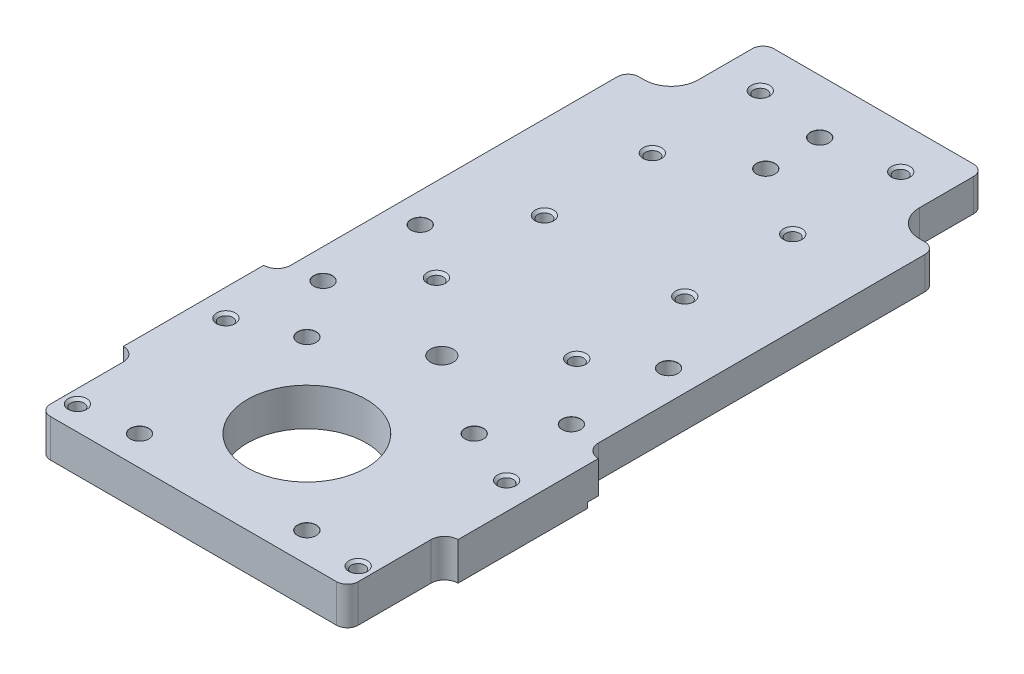
SolidWorks part; units mm, degrees
ref_plane "Top" through (0, 0, 0) normal (0, 0, 1) x (1, 0, 0)
ref_plane "Front" through (0, 0, 0) normal (0, 1, 0) x (1, 0, 0)
ref_plane "Right" through (0, 0, 0) normal (1, 0, 0) x (0, 0, -1)
sketch "Plate Main Sketch" plane through (-158.0855, 0, 24.6791) normal (0, 1, 0) x (-1, 0, 0)
  line L1 (-178.5855, -24.6791) -> (-137.5855, -24.6791)
  line L2 (-127.0855, 57.3209) -> (-127.0855, 83.3209)
  line L3 (-129.5855, 101.3209) -> (-186.5855, 101.3209)
  line L4 (-129.5855, 101.3209) -> (-129.5855, 85.8209)
  line L5 (-158.0855, 101.3209) -> (-158.0855, -24.6791) construction
  line L6 (-178.5855, -12.6791) -> (-178.5855, -24.6791)
  line L7 (-129.5855, 54.8209) -> (-129.5855, -7.6791)
  line L8 (-129.5855, -7.6791) -> (-132.5855, -7.6791)
  line L9 (-137.5855, -12.6791) -> (-137.5855, -24.6791)
  line L10 (-186.5855, -7.6791) -> (-183.5855, -7.6791)
  line L11 (-186.5855, 54.8209) -> (-186.5855, -7.6791)
  line L12 (-189.0855, 57.3209) -> (-189.0855, 83.3209)
  line L13 (-186.5855, 101.3209) -> (-186.5855, 85.8209)
  arc A0 (-129.5855, 85.8209) -> (-127.0855, 83.3209) centre (-127.0855, 85.8209) ccw
  arc A1 (-129.5855, 54.8209) -> (-127.0855, 57.3209) centre (-127.0855, 54.8209) cw
  arc A2 (-132.5855, -7.6791) -> (-137.5855, -12.6791) centre (-132.5855, -12.6791) ccw
  arc A3 (-183.5855, -7.6791) -> (-178.5855, -12.6791) centre (-183.5855, -12.6791) cw
  arc A4 (-186.5855, 54.8209) -> (-189.0855, 57.3209) centre (-189.0855, 54.8209) ccw
  arc A5 (-186.5855, 85.8209) -> (-189.0855, 83.3209) centre (-189.0855, 85.8209) cw
  circle A18 centre (-158.0855, 80.3209) radius 11
  circle A19 centre (-158.0855, 55.3209) radius 2.1117
  dimension "D2" = 5
  dimension "D8" = 22
  dimension "D1" = 2.5
  dimension "D3" = 62
  dimension "D4" = 126
  dimension "D5" = 18
  dimension "D6" = 44
  dimension "D15" = 21
  dimension "D16" = 46
  dimension "D17" = 8
  dimension "D7" = 109
extrude "Extrude Plate Main" add sketch "Plate Main Sketch" along normal blind 7
fillet "Fillet1" radius 2 6 edges at (-28.5, 3.5, 126) (-28.5, 3.5, 17) (-20.5, 3.5, 0) (20.5, 3.5, 0) (28.5, 3.5, 17) (28.5, 3.5, 126)
sketch "Reccess Sketch" plane through (0, 0, 0) normal (0, 1, 0) x (1, 0, 0)
  line L0 (-8.25, 0) -> (-8.25, -81)
  line L1 (-11.25, -84) -> (-31, -84)
  line L2 (-31, -84) -> (-31, 0)
  line L3 (-31, 0) -> (-8.25, 0)
  line L4 (0, 0) -> (0, -84) construction
  line L5 (31, 0) -> (8.25, 0)
  line L6 (8.25, 0) -> (8.25, -81)
  line L7 (31, -84) -> (31, 0)
  line L8 (11.25, -84) -> (31, -84)
  arc A0 (-8.25, -81) -> (-11.25, -84) centre (-11.25, -81) cw
  arc A1 (8.25, -81) -> (11.25, -84) centre (11.25, -81) ccw
  point P7 (-8.25, -84)
  dimension "D4" = 3
  dimension "D1" = 84
  dimension "D2" = 31
  dimension "D3" = 22.75
hole_wizard "M3x0.5 Tapped Hole3" positions "Sketch12" profile "Sketch13" tap size "M3x0.5" standard "ANSI Metric" end condition through all
sketch "Sketch12" plane through (0, 0, 0) normal (0, -1, 0) x (-1, 0, 0)
  line L0 (-13, -8) -> (-13, -68) construction
  line L2 (13, -68) -> (13, -8) construction
  line L4 (26, -121.5) -> (-26, -121.5) construction
  line L5 (-26, -121.5) -> (-26, -94) construction
  line L6 (-26, -94) -> (26, -94) construction
  line L7 (26, -94) -> (26, -121.5) construction
  line L11 (31, -126) -> (-31, -126) construction
  line L12 (31, -126) -> (31, 0) construction
  line L13 (31, 0) -> (-31, 0) construction
  line L14 (-31, -126) -> (-31, 0) construction
  line L15 (0, 0) -> (0, -126) construction
  line L16 (31, -63) -> (-31, -63) construction
  point P0 (-26, -121.5)
  point P2 (-26, -94)
  point P4 (26, -94)
  point P8 (13, -68)
  point P10 (13, -48)
  point P12 (13, -28)
  point P14 (13, -8)
  point P16 (-13, -8)
  point P18 (-13, -28)
  point P20 (-13, -48)
  point P22 (-13, -68)
  point P477 (26, -121.5)
  dimension "D1" = 126
  dimension "D2" = 62
  dimension "D3" = 118
  dimension "D4" = 98
  dimension "D5" = 78
  dimension "D6" = 58
  dimension "D7" = 18
  dimension "D8" = 18
  dimension "D9" = 5
  dimension "D10" = 5
  dimension "D11" = 4.5
  dimension "D12" = 32
sketch "Sketch13" plane through (26, 0, 121.5) normal (1, 0, 0) x (0, 0, -1)
  line L0 (0, 0) -> (0, 7)
  line L1 (0, 7) -> (1.725, 7)
  line L2 (1.25, 6.525) -> (1.25, 0)
  line L5 (1.25, 0) -> (0, 0)
  line L7 (1.725, 7) -> (1.25, 6.525)
  line L8 (-1.725, 7) -> (-1.25, 6.525) construction
  line L11 (0, -6.35) -> (0, 107.95) construction
  dimension "Thru Tap Drill Dia." = 2.5
  dimension "Thru Tap Drill Depth" = 7
  dimension "Far C'Sink Dia." = 3.45
  dimension "Far C'Sink Angle" = 90
cosmetic thread "Hole Thread54" parameters "D2"=3
cosmetic thread "Hole Thread55" parameters "D2"=3
cosmetic thread "Hole Thread56" parameters "D2"=3
cosmetic thread "Hole Thread57" parameters "D2"=3
cosmetic thread "Hole Thread58" parameters "D2"=3
cosmetic thread "Hole Thread59" parameters "D2"=3
cosmetic thread "Hole Thread60" parameters "D2"=3
cosmetic thread "Hole Thread61" parameters "D2"=3
cosmetic thread "Hole Thread62" parameters "D2"=3
cosmetic thread "Hole Thread63" parameters "D2"=3
cosmetic thread "Hole Thread64" parameters "D2"=3
cosmetic thread "Hole Thread65" parameters "D2"=3
hole_wizard "CBORE for M3 SHCS1" positions "Sketch4" profile "Sketch5" counterbore size "M3" standard "ANSI Metric" end condition through all
sketch "Sketch4" plane through (0, 0, 0) normal (0, -1, 0) x (-1, 0, 0)
  line L0 (31, -126) -> (-31, -126) construction
  line L1 (-31, -126) -> (-31, 0) construction
  line L2 (-31, 0) -> (31, 0) construction
  line L3 (31, 0) -> (31, -126) construction
  line L5 (15.5, -120.5) -> (-15.5, -120.5) construction
  line L6 (-15.5, -120.5) -> (-15.5, -89.5) construction
  line L7 (-15.5, -89.5) -> (15.5, -89.5) construction
  line L8 (15.5, -89.5) -> (15.5, -120.5) construction
  line L10 (0, -126) -> (0, 0) construction
  point P0 (15.5, -120.5)
  point P3 (-15.5, -120.5)
  point P6 (-15.5, -89.5)
  point P9 (15.5, -89.5)
  point P12 (23, -79)
  point P15 (-23, -79)
  point P18 (-23, -61)
  point P21 (23, -61)
  point P24 (0, -20)
  point P27 (0, -10)
  point P42 (0, 0)
  point P65 (0, -120.5)
  dimension "D1" = 126
  dimension "D2" = 62
  dimension "D3" = 31
  dimension "D4" = 31
  dimension "D5" = 5.5
  dimension "D6" = 47
  dimension "D7" = 65
  dimension "D8" = 106
  dimension "D9" = 116
  dimension "D10" = 8
  dimension "D11" = 8
sketch "Sketch5" plane through (-15.5, 0, 120.5) normal (1, 0, 0) x (0, 0, -1)
  line L0 (0, 0) -> (0, 7)
  line L1 (1.7, 6.975) -> (1.725, 7)
  line L2 (1.7, 6.975) -> (1.7, 4.5)
  line L3 (1.7, 4.5) -> (3, 4.5)
  line L4 (3, 4.5) -> (3, 0)
  line L5 (3, 0) -> (0, 0)
  line L11 (0, -6.35) -> (0, 107.95) construction
  line L12 (1.725, 7) -> (0, 7)
  line L13 (-1.7, 6.975) -> (-1.725, 7) construction
  dimension "Thru Hole Dia." = 3.4
  dimension "Thru Hole Depth" = 7
  dimension "C'Bore Dia." = 6
  dimension "C'Bore Depth" = 4.5
  dimension "Far C'Sink Dia." = 3.45
  dimension "Far C'Sink Angle" = 90
extrude "Cut Recess" cut sketch "Reccess Sketch" along normal blind 1
sketch "Sketch7" plane through (158.0855, -24.6791, 0) normal (0, 0, -1) x (1, 0, 0)
  line L1 (-178.5855, -24.6791) -> (-137.5855, -24.6791) construction
  line L2 (-127.0855, 57.3209) -> (-127.0855, 83.3209) construction
  line L3 (-129.5855, 101.3209) -> (-186.5855, 101.3209) construction
  line L4 (-129.5855, 101.3209) -> (-129.5855, 85.8209) construction
  line L5 (-158.0855, 101.3209) -> (-158.0855, -24.6791) construction
  line L6 (-178.5855, -12.4678) -> (-178.5855, -24.6791) construction
  line L7 (-129.5855, 54.8209) -> (-129.5855, -7.6791) construction
  line L8 (-129.5855, -7.6791) -> (-132.7968, -7.6791) construction
  line L9 (-137.5855, -12.4678) -> (-137.5855, -24.6791) construction
  line L10 (-186.5855, -7.6791) -> (-183.3743, -7.6791) construction
  line L11 (-186.5855, 54.8209) -> (-186.5855, -7.6791) construction
  line L12 (-189.0855, 57.3209) -> (-189.0855, 83.3209) construction
  line L13 (-186.5855, 101.3209) -> (-186.5855, 85.8209) construction
  line L14 (-173.5855, 95.8209) -> (-142.5855, 95.8209) construction
  line L15 (-142.5855, 95.8209) -> (-142.5855, 64.8209) construction
  line L16 (-142.5855, 64.8209) -> (-173.5855, 64.8209) construction
  line L17 (-173.5855, 64.8209) -> (-173.5855, 95.8209) construction
  arc A0 (-129.5855, 85.8209) -> (-127.0855, 83.3209) centre (-127.0855, 85.8209) ccw construction
  arc A1 (-129.5855, 54.8209) -> (-127.0855, 57.3209) centre (-127.0855, 54.8209) cw construction
  arc A2 (-132.7968, -7.6791) -> (-137.5855, -12.4678) centre (-132.7968, -12.4678) ccw construction
  arc A3 (-183.3743, -7.6791) -> (-178.5855, -12.4678) centre (-183.3743, -12.4678) cw construction
  arc A4 (-186.5855, 54.8209) -> (-189.0855, 57.3209) centre (-189.0855, 54.8209) ccw construction
  arc A5 (-186.5855, 85.8209) -> (-189.0855, 83.3209) centre (-189.0855, 85.8209) cw construction
  circle A6 centre (-142.5855, 95.8209) radius 0.8649
  circle A7 centre (-142.5855, 64.8209) radius 0.8649
  circle A8 centre (-173.5855, 64.8209) radius 0.8649
  circle A9 centre (-173.5855, 95.8209) radius 0.8649
  circle A20 centre (-158.0855, -4.6791) radius 0.9359
  circle A21 centre (-158.0855, -14.6791) radius 1.008
  circle A22 centre (-176.6802, 54.3209) radius 1.5374
  circle A23 centre (-176.6802, 36.3209) radius 1.5374
  circle A24 centre (-142.5855, 54.3209) radius 1.5374
  circle A25 centre (-142.5855, 36.3209) radius 1.5374
  dimension "D3" = 62
  dimension "D1" = 2.5
  dimension "D2" = 15.5
  dimension "D8" = 106
  dimension "D11" = 116
  dimension "D12" = 47
  dimension "D4" = 126
  dimension "D5" = 18
  dimension "D6" = 44
  dimension "D7" = 109
  dimension "D9" = 5.5
  dimension "D10" = 36.5
  dimension "D13" = 65
  dimension "D17" = 8
equation "\"M2 Close Fit Hole\"= 2.2"
equation "\"M2.5 Close Fit Hole\"= 2.7"
equation "\"M3 Close Fit Hole\"= 3.2"
equation "\"M4 Close Fit Hole\"= 4.3"
equation "\"M5 Close Fit Hole\"= 5.3"
equation "\"M6 Close Fit Hole\"= 6.3"
equation "\"M7 Close Fit Hole\"= 7.4"
equation "\"M8 Close Fit Hole\"= 8.4"
equation "\"M2 Tap Hole 75%\"= 1.6"
equation "\"M3 Tap Hole 75%\"= 2.5"
equation "\"M4 Tap Hole 75%\"= 3.3"
equation "\"M5 Tap Hole 75%\"= 4.2"
equation "\"M6 Tap Hole 75%\"= 5"
equation "\"M7 Tap Hole 75%\"= 6"
equation "\"M8 Tap Hole 75%\"= 6.8"
equation "\"Bracket Width\"= 62mm"
equation "\"D3@Plate Main Sketch\"=\"Bracket Width\""
equation "\"Bracket Height\"= 126mm"
equation "\"D4@Plate Main Sketch\"=\"Bracket Height\""
equation "\"D1@Sketch4\"=\"Bracket Height\""
equation "\"D2@Sketch4\"=\"Bracket Width\""
equation "\"D1@Sketch12\"=\"Bracket Height\""
equation "\"D2@Sketch12\"=\"Bracket Width\""
equation "\"D2@Reccess Sketch\" = 0.5 * \"Bracket Width\""
